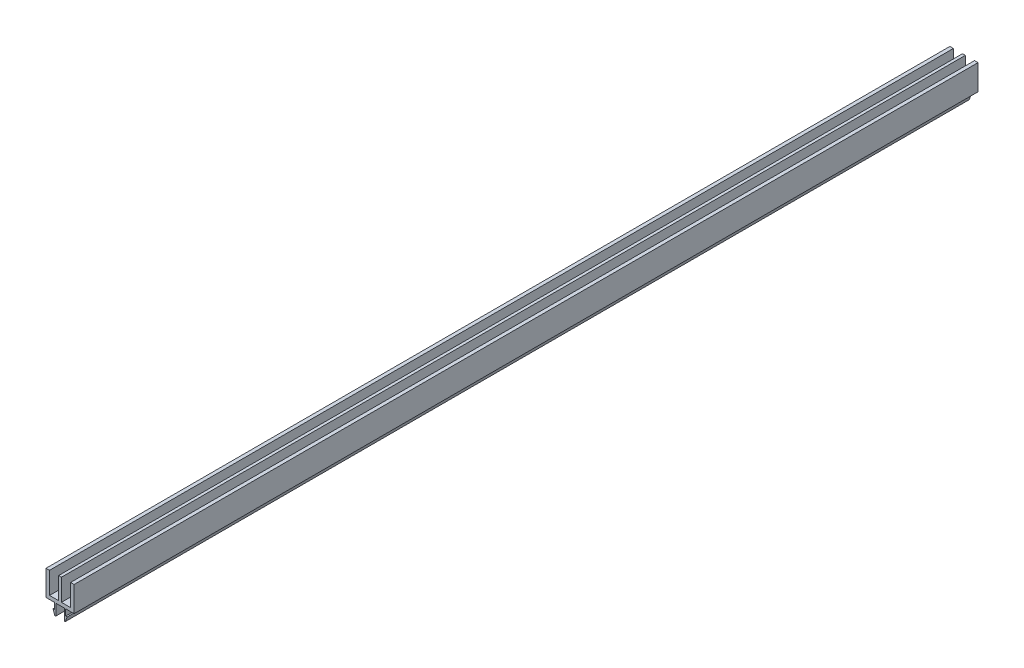
SolidWorks part; units mm, degrees
ref_plane "Plan de face" through (0, 0, 0) normal (0, 0, 1) x (1, 0, 0)
ref_plane "Plan de dessus" through (0, 0, 0) normal (0, 1, 0) x (1, 0, 0)
ref_plane "Plan de droite" through (0, 0, 0) normal (1, 0, 0) x (0, 0, -1)
ref_plane "Plan1" through (0, 0, 50) normal (0, 0, 1) x (1, 0, 0)
sketch "Esquisse1" plane through (0, 0, 50) normal (0, 0, 1) x (1, 0, 0)
  line L0 (-1, 2.5) -> (-7.5, 2.5)
  line L1 (-7.5, 2.5) -> (-7.5, 18)
  line L2 (-7.5, 18) -> (-10, 18)
  line L3 (-10, 18) -> (-10, 0)
  line L4 (-10, 0) -> (-4, 0)
  line L5 (-4, 0) -> (-4, -4.5)
  line L6 (-4, -4.5) -> (-5, -4.5)
  line L7 (-5, -4.5) -> (-3.75, -8)
  line L8 (-3.75, -8) -> (-3, -8)
  line L9 (-3, -8) -> (-3, 0)
  line L10 (-3, 0) -> (3, 0)
  line L11 (3, 0) -> (3, -8)
  line L12 (3, -8) -> (3.75, -8)
  line L13 (3.75, -8) -> (5, -4.5)
  line L14 (5, -4.5) -> (4, -4.5)
  line L15 (4, -4.5) -> (4, 0)
  line L16 (4, 0) -> (10, 0)
  line L17 (10, 0) -> (10, 18)
  line L18 (10, 18) -> (7.5, 18)
  line L19 (7.5, 18) -> (7.5, 2.5)
  line L20 (7.5, 2.5) -> (1, 2.5)
  line L21 (1, 2.5) -> (1, 18)
  line L22 (1, 18) -> (-1, 18)
  line L23 (-1, 18) -> (-1, 2.5)
extrude "Boss.-Extru.1" add sketch "Esquisse1" against normal blind 643.09
